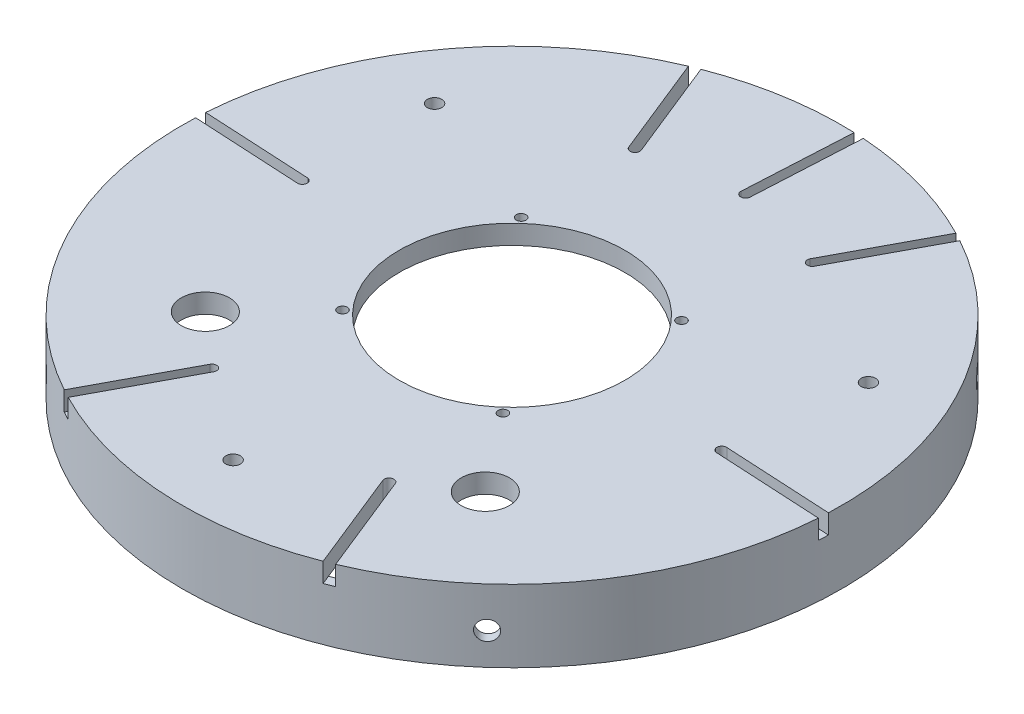
SolidWorks part; units mm, degrees
material "6061 Alloy"
ref_plane "Front Plane" through (0, 0, 0) normal (0, 0, 1) x (1, 0, 0)
ref_plane "Top Plane" through (0, 0, 0) normal (0, 1, 0) x (1, 0, 0)
ref_plane "Right Plane" through (0, 0, 0) normal (1, 0, 0) x (0, 0, -1)
sketch "Sketch1" plane through (0, 0, 0) normal (0, 1, 0) x (-0.9986, 0, -0.0535)
  line L0 (55.4987, 41.0091) -> (55.4987, 34.0091) construction
  line L2 (55.4987, -32.3449) -> (55.4987, -2.3278) construction
  circle A1 centre (55.4987, -32.3449) radius 68.37
  circle A3 centre (55.4987, -32.3449) radius 23.401
extrude "Boss-Extrude1" add sketch "Sketch1" along normal blind 2
sketch "Sketch3" plane through (0, 2, 0) normal (0, 1, 0) x (1, 0, 0)
  circle A0 centre (-53.6871, 35.2703) radius 68.37
  circle A1 centre (-53.6871, 35.2703) radius 66.37
extrude "Boss-Extrude2" add sketch "Sketch3" against normal blind 13
sketch "Sketch24" [suppressed] plane through (0, 4.3, 0) normal (0, 1, 0) x (1, 0, 0)
  line L0 (-34.4111, 2.0274) -> (-34.9466, -7.9582) construction
  line L1 (25.902, -11.2211) -> (26.4375, -1.2355) construction
  point P0 (-34.6788, -2.9654)
  point P1 (26.1698, -6.2283)
sketch "Sketch25" [suppressed] plane through (0, 0, 0) normal (0, -1, 0) x (1, 0, 0)
  point P0 (-34.6788, 2.9654)
  point P1 (26.1698, 6.2283)
ref_plane "Plane1" [suppressed] through (-0.258, 0, 4.8112) normal (0.0535, 0, -0.9986) x (-0.9986, 0, -0.0535)
sketch "Sketch29" [suppressed] plane through (0, 4.3, 0) normal (0, 1, 0) x (1, 0, 0)
  arc A0 (18.841, -0.8281) -> (-26.8146, 1.6201) centre (-4.2545, -4.5968) ccw construction
  arc A1 (-27.3501, -8.3656) -> (18.3055, -10.8138) centre (-4.2545, -4.5968) ccw construction
  point P0 (-3.0015, 18.7706)
  point P1 (-5.5076, -27.9643)
sketch "Sketch30" [suppressed] plane through (0, 0, 0) normal (0, -1, 0) x (1, 0, 0)
  point P0 (-5.5076, 27.9643)
  point P1 (-3.0015, -18.7706)
ref_plane "Plane2" [suppressed] through (-3.9965, 0, -0.2143) normal (-0.9986, 0, -0.0535) x (-0.0535, 0, 0.9986)
sketch "Sketch35" [suppressed] plane through (0, 0, 0) normal (0, 1, 0) x (1, 0, 0)
  line L0 (-3.8699, 2.5759) -> (-4.1232, -2.1473) construction
  line L1 (2.1036, -4.9378) -> (-2.6196, -4.6845) construction
  line L2 (20.5267, 17.662) -> (-4.2545, -4.5968) construction
  line L3 (-4.2545, -4.5968) -> (-31.1135, -28.7219) construction
  arc A1 (-27.3501, -8.3656) -> (18.3055, -10.8138) centre (-4.2545, -4.5968) ccw construction
  point P0 (-4.2545, -4.5968)
  point P8 (20.5267, 17.662)
  point P10 (-21.6638, -20.2341)
sketch "Sketch36" [suppressed] plane through (0, 4.3, 0) normal (0, 1, 0) x (1, 0, 0)
  point P0 (20.5267, 17.662)
ref_plane "Plane3" [suppressed] through (0.3855, 0, 0.4291) normal (0.6682, 0, 0.744) x (0.744, 0, -0.6682)
sketch "Sketch37" [suppressed] plane through (0, 4.3, 0) normal (0, 1, 0) x (1, 0, 0)
  line L1 (-26.6296, 20.3138) -> (-4.2545, -4.5968) construction
  line L2 (-4.2545, -4.5968) -> (20.7564, -32.4421) construction
  point P0 (-4.2545, -4.5968)
  point P7 (-26.6296, 20.3138)
sketch "Sketch39" [suppressed] plane through (0, 0, 0) normal (0, -1, 0) x (1, 0, 0)
  point P0 (-26.6296, -20.3138)
ref_plane "Plane4" [suppressed] through (-4.64, 0, 4.1677) normal (-0.744, 0, 0.6682) x (0.6682, 0, 0.744)
sketch "Sketch40" [suppressed] plane through (0.3855, 0, 0.4291) normal (0.6682, 0, 0.744) x (0.744, 0, -0.6682)
  circle A0 centre (-6.2369, -3.85) radius 2
extrude "Cut-Extrude27" [suppressed] cut sketch "Sketch40" against normal through all
pattern_circular "CirPattern2" [suppressed] count 4 over 360
sketch "Sketch58" plane through (0, 2, 0) normal (0, 1, 0) x (1, 0, 0)
  line L2 (-12.7238, 29.0656) -> (-12.2954, 37.0565)
  line L3 (-12.2954, 37.0565) -> (-7.3025, 36.7887)
  line L4 (-7.3025, 36.7887) -> (-7.731, 28.7979)
  line L5 (-7.731, 28.7979) -> (-12.7238, 29.0656)
sketch "Sketch60" plane through (0, 2, 0) normal (0, 1, 0) x (1, 0, 0)
  line L0 (-52.2437, 62.1872) -> (-55.1305, 8.3534) construction
  line L1 (-84.1539, 36.904) -> (-23.2203, 33.6365) construction
  line L4 (-73.7408, 17.2578) -> (-104.5394, -10.4059) construction
  line L5 (-53.6871, 35.2703) -> (-73.7408, 17.2578) construction
  line L6 (-71.6996, 55.324) -> (-99.3633, 86.1226) construction
  line L7 (-53.6871, 35.2703) -> (-71.6996, 55.324) construction
  line L8 (-33.6334, 53.2828) -> (-2.8348, 80.9464) construction
  line L9 (-53.6871, 35.2703) -> (-33.6334, 53.2828) construction
  line L10 (-35.6746, 15.2165) -> (-8.0109, -15.5821) construction
  line L11 (-53.6871, 35.2703) -> (-35.6746, 15.2165) construction
  line L12 (-73.7408, 17.2578) -> (-104.5394, -10.4059) construction
  line L13 (-53.6871, 35.2703) -> (-73.7408, 17.2578) construction
  arc A1 (-55.1305, 8.3534) -> (-80.604, 36.7136) centre (-53.6871, 35.2703) cw
sketch "Sketch62" plane through (0, 0, 0) normal (0, -1, 0) x (1, 0, 0)
  line L0 (-8.0109, 15.5821) -> (-99.3633, -86.1226) construction
  line L1 (-104.5394, 10.4059) -> (-2.8348, -80.9464) construction
  point P9 (-53.6871, -35.2703)
ref_plane "Plane5" through (-41.5069, 0, -46.2106) normal (0.6682, 0, 0.744) x (0.744, 0, -0.6682)
ref_plane "Plane6" through (-12.1802, 0, 10.9404) normal (0.744, 0, -0.6682) x (-0.6682, 0, -0.744)
sketch "Sketch63" plane through (-41.5069, 0, -46.2106) normal (0.6682, 0, 0.744) x (0.744, 0, -0.6682)
  line L0 (-84.7262, 0) -> (51.9818, 0) construction
  line L3 (-16.3722, 0) -> (-16.3722, -8.7) construction
  circle A0 centre (-16.3722, -4.35) radius 2
extrude "Cut-Extrude40" cut sketch "Sketch63" against normal through all and the other way through all
sketch "Sketch64" plane through (-12.1802, 0, 10.9404) normal (0.744, 0, -0.6682) x (-0.6682, 0, -0.744)
  line L0 (-6.2392, 0) -> (130.4688, 0) construction
  line L3 (62.1148, 0) -> (62.1148, -8.7) construction
  circle A0 centre (62.1148, -4.35) radius 2
extrude "Cut-Extrude41" cut sketch "Sketch64" against normal through all and the other way through all
sketch "Sketch65" plane through (0, 2, 0) normal (0, -1, 0) x (1, 0, 0)
  line L2 (1.1947, -31.5296) -> (-6.7555, -31.9265)
  line L3 (0.4048, -1118.9656) -> (-50.8954, -91.2006) construction
  line L4 (1.2944, -33.5271) -> (-6.7555, -33.9289)
  line L5 (-108.5689, -39.0109) -> (-100.6187, -38.6141)
  line L6 (-108.6686, -37.0134) -> (-100.6187, -36.6116)
  line L7 (-49.9465, -90.152) -> (-50.3433, -82.2019)
  line L8 (-51.944, -90.2517) -> (-52.3458, -82.2019)
  line L16 (-57.4277, 19.6115) -> (-57.0309, 11.6614) [skipped]
  line L17 (-55.4302, 19.7112) -> (-55.0284, 11.6614) [skipped]
  arc A2 (1.2944, -33.5271) -> (1.1947, -31.5296) centre (1.2445, -32.5284) ccw
  arc A3 (-6.7555, -33.9289) -> (-6.7555, -31.9265) centre (-6.8055, -32.9277) cw
  arc A4 (-51.944, -90.2517) -> (-49.9465, -90.152) centre (-50.9452, -90.2019) ccw
  arc A5 (-52.3458, -82.2019) -> (-50.3433, -82.2019) centre (-51.3445, -82.1519) cw
  arc A6 (-108.6686, -37.0134) -> (-108.5689, -39.0109) centre (-108.6187, -38.0121) ccw
  arc A7 (-100.6187, -36.6116) -> (-100.6187, -38.6141) centre (-100.5687, -37.6128) cw
  arc A16 (-55.4302, 19.7112) -> (-57.4277, 19.6115) centre (-56.429, 19.6614) ccw [skipped]
  arc A17 (-55.0284, 11.6614) -> (-57.0309, 11.6614) centre (-56.0297, 11.6114) cw [skipped]
  dimension "D1" = 4
sketch "Sketch67" plane through (0, 2, 0) normal (0, 1, 0) x (1, 0, 0)
  line L0 (-99.6611, 37.7404) -> (-7.7126, 32.8099) construction
  line L1 (-51.2218, 81.2445) -> (-56.1524, -10.704) construction
  line L2 (-47.8311, 125.7094) -> (-49.8283, 125.8165)
  line L3 (-144.1262, 41.1262) -> (-144.2333, 39.1291)
  line L4 (-99.6075, 38.739) -> (-144.1262, 41.1262)
  line L5 (-99.7146, 36.7419) -> (-144.2333, 39.1291)
  line L6 (-50.2184, 81.1907) -> (-47.8311, 125.7094)
  line L7 (-52.2155, 81.2978) -> (-49.8283, 125.8165)
  line L8 (36.752, 29.4143) -> (36.8591, 31.4114)
  line L9 (-7.7667, 31.8015) -> (36.752, 29.4143)
  line L10 (-7.6596, 33.7987) -> (36.8591, 31.4114)
  line L49 (-59.5431, -55.1689) -> (-57.5459, -55.276) [skipped]
  line L50 (-57.1558, -10.6501) -> (-59.5431, -55.1689) [skipped]
  line L51 (-55.1587, -10.7572) -> (-57.5459, -55.276) [skipped]
  arc A1 (-99.6075, 38.739) -> (-99.7146, 36.7419) centre (-99.6611, 37.7404) cw
  arc A2 (-50.2184, 81.1907) -> (-52.2155, 81.2978) centre (-51.2169, 81.2442) cw
  arc A3 (-7.7667, 31.8015) -> (-7.6596, 33.7987) centre (-7.7132, 32.8001) cw
  arc A8 (-57.1558, -10.6501) -> (-55.1587, -10.7572) centre (-56.1573, -10.7037) cw [skipped]
  dimension "D1" = 4
extrude "Cut-Extrude45" cut sketch "Sketch67" against normal blind 2
sketch "Sketch70" plane through (0, 2, 0) normal (0, 1, 0) x (1, 0, 0)
  line L0 (-51.2169, 81.2442) -> (-53.6871, 35.2703) construction
  line L1 (-99.6611, 37.7404) -> (-7.7132, 32.8001) construction
  line L2 (-53.6871, 35.2703) -> (-56.5307, -17.6534) construction
  circle A0 centre (-99.7745, 65.2862) radius 1.5
  circle A1 centre (-56.638, -19.6505) radius 1.5
  circle A2 centre (-4.6489, 60.1751) radius 1.5
  dimension "D1" = 3
  dimension "D2" = 3
sketch "Sketch72" plane through (0, 2, 0) normal (0, 1, 0) x (1, 0, 0)
  line L0 (-51.2169, 81.2442) -> (-56.638, -19.6505) construction
  line L1 (-99.6611, 37.7404) -> (-7.7132, 32.8001) construction
sketch "Sketch73" plane through (0, 2, 0) normal (0, -1, 0) x (1, 0, 0)
  circle A0 centre (-72.2141, -18.6326) radius 1
  circle A1 centre (-37.0495, -16.7433) radius 1
  circle A2 centre (-35.1601, -51.9079) radius 1
  circle A3 centre (-70.3247, -53.7973) radius 1
extrude "Cut-Extrude47" cut sketch "Sketch73" along normal blind 10
extrude "Cut-Extrude48" cut sketch "Sketch70" against normal blind 10
extrude "Cut-Extrude49" cut sketch "Sketch74" against normal blind 10
sketch "Sketch74" plane through (19.5625, 3, -2.0536) normal (0, 1, 0) x (1, 0, 0)
  line L0 (-73.2496, 33.2167) -> (-76.2005, -21.7041) construction
  line L1 (-73.2496, 33.2167) -> (-44.3242, -1.2553) construction
  line L2 (-73.2496, 33.2167) -> (-105.7022, 2.0425) construction
  circle A0 centre (-105.7022, 2.0425) radius 5
  circle A1 centre (-44.3242, -1.2553) radius 5
sketch "Sketch75" plane through (0, 2, 0) normal (0, 1, 0) x (1, 0, 0)
  line L0 (-50.0757, 102.5274) -> (-51.2185, 81.2443) construction
  line L1 (-120.9442, 38.8817) -> (13.57, 31.6588) construction
  line L2 (-86.2666, -23.6885) -> (-88.9936, -28.8014)
  line L3 (-22.8723, 95.1703) -> (-32.9078, 76.3546)
  line L4 (-21.1076, 94.229) -> (-31.1431, 75.4134)
  line L5 (-88.9936, -28.8014) -> (-87.2289, -29.7426)
  line L6 (-53.5602, 37.6331) -> (-58.8341, -60.585) construction
  line L7 (-52.5853, 35.2111) -> (-52.8048, 34.7997)
  line L8 (-84.5019, -24.6297) -> (-87.2289, -29.7426)
  line L9 (-79.7658, 97.3787) -> (-83.5737, 106.8386)
  line L10 (-53.5602, 37.6331) -> (-54.5694, 35.7409)
  line L11 (-77.9105, 98.1256) -> (-82.0529, 108.4166)
  line L12 (-79.7658, 97.3787) -> (-71.8029, 77.5967)
  line L13 (-22.8723, 95.1703) -> (-17.9091, 104.4757)
  line L14 (-77.9105, 98.1256) -> (-69.9475, 78.3435)
  line L15 (-27.6084, -26.8382) -> (-35.5714, -7.0562)
  line L16 (-21.1076, 94.229) -> (-18.0109, 100.0352)
  line L17 (-29.4638, -27.5851) -> (-37.4267, -7.803)
  line L18 (-29.4638, -27.5851) -> (-27.0828, -33.5)
  line L19 (-84.5019, -24.6297) -> (-74.4664, -5.8141)
  line L20 (-86.2666, -23.6885) -> (-76.2311, -4.8729)
  line L21 (-27.6084, -26.8382) -> (-25.2275, -32.7531)
  line L22 (-25.2275, -32.7531) -> (-27.0828, -33.5)
  line L23 (-83.5737, 106.8386) -> (-82.0529, 108.4166)
  line L24 (-17.9091, 104.4757) -> (-18.0109, 100.0352)
  arc A3 (-32.9078, 76.3546) -> (-31.1431, 75.4134) centre (-32.0254, 75.884) ccw
  arc A4 (-69.9475, 78.3435) -> (-71.8029, 77.5967) centre (-70.8752, 77.9701) cw
  arc A5 (-37.4267, -7.803) -> (-35.5714, -7.0562) centre (-36.499, -7.4296) cw
  arc A6 (-74.4664, -5.8141) -> (-76.2311, -4.8729) centre (-75.3488, -5.3435) ccw
extrude "Cut-Extrude51" cut sketch "Sketch75" against normal blind 2
sketch "Sketch80" plane through (0, 2, 0) normal (0, 1, 0) x (1, 0, 0)
  line L0 (-121.8978, 39.9343) -> (-99.6075, 38.739)
  line L1 (-122.0051, 37.9371) -> (-99.7146, 36.7419)
  line L2 (-78.2871, 99.0613) -> (-69.9475, 78.3435)
  line L3 (-80.1424, 98.3145) -> (-71.8029, 77.5967)
  line L4 (-51.0202, 103.5882) -> (-52.2155, 81.2978)
  line L5 (-49.0231, 103.481) -> (-50.2184, 81.1907)
  line L6 (-22.3976, 96.0603) -> (-32.9078, 76.3546)
  line L7 (-20.6329, 95.119) -> (-31.1431, 75.4134)
  line L8 (-20.6329, 95.119) -> (-31.1431, 75.4134) construction
  line L9 (14.6309, 32.6034) -> (-7.6596, 33.7987)
  line L10 (-7.7667, 31.8015) -> (14.5236, 30.6063)
  line L11 (-86.7413, -24.5785) -> (-76.2311, -4.8729)
  line L12 (-74.4664, -5.8141) -> (-84.9766, -25.5197)
  line L13 (-37.4267, -7.803) -> (-29.0871, -28.5208)
  line L14 (-35.5714, -7.0562) -> (-27.2318, -27.7739)
  arc A0 (-80.1424, 98.3145) -> (-121.8978, 39.9343) centre (-53.6871, 35.2703) ccw
  circle A1 centre (-99.7745, 65.2862) radius 1.5
  circle A2 centre (-4.6489, 60.1751) radius 1.5
  circle A3 centre (-24.7617, 0.7983) radius 5
  circle A4 centre (-86.1397, 4.0961) radius 5
  circle A5 centre (-72.2141, 18.6326) radius 1
  circle A6 centre (-53.6871, 35.2703) radius 23.401
  circle A7 centre (-37.0495, 16.7433) radius 1
  circle A8 centre (-35.1601, 51.9079) radius 1
  circle A9 centre (-70.3247, 53.7973) radius 1
  arc A10 (-32.9078, 76.3546) -> (-31.1431, 75.4134) centre (-32.0254, 75.884) ccw construction
  circle A11 centre (-56.638, -19.6505) radius 1.5
  arc A12 (-7.7667, 31.8015) -> (-7.6596, 33.7987) centre (-7.7132, 32.8001) cw
  arc A13 (-32.9078, 76.3546) -> (-31.1431, 75.4134) centre (-32.0254, 75.884) ccw
  arc A14 (-52.2155, 81.2978) -> (-50.2184, 81.1907) centre (-51.2169, 81.2442) ccw
  arc A15 (-69.9475, 78.3435) -> (-71.8029, 77.5967) centre (-70.8752, 77.9701) cw
  arc A16 (-99.6075, 38.739) -> (-99.7146, 36.7419) centre (-99.6611, 37.7404) cw
  arc A17 (-74.4664, -5.8141) -> (-76.2311, -4.8729) centre (-75.3488, -5.3435) ccw
  arc A18 (-51.0202, 103.5882) -> (-78.2871, 99.0613) centre (-53.6871, 35.2703) ccw
  arc A19 (-76.2311, -4.8729) -> (-74.4664, -5.8141) centre (-75.3488, -5.3435) cw
  arc A20 (-35.5714, -7.0562) -> (-37.4267, -7.803) centre (-36.499, -7.4296) ccw
  arc A21 (-22.3976, 96.0603) -> (-49.0231, 103.481) centre (-53.6871, 35.2703) ccw
  arc A22 (14.6309, 32.6034) -> (-20.6329, 95.119) centre (-53.6871, 35.2703) ccw
  arc A23 (-27.2318, -27.7739) -> (14.5236, 30.6063) centre (-53.6871, 35.2703) ccw
  arc A24 (-84.9766, -25.5197) -> (-29.0871, -28.5208) centre (-53.6871, 35.2703) ccw
  arc A25 (-122.0051, 37.9371) -> (-86.7413, -24.5785) centre (-53.6871, 35.2703) ccw
  circle M1 centre (-24.7617, 0.7983) radius 5
  circle M2 centre (-86.1397, 4.0961) radius 5
  circle M3 centre (-4.6489, 60.1751) radius 1.5
  circle M4 centre (-99.7745, 65.2862) radius 1.5
  circle M5 centre (-56.638, -19.6505) radius 1.5
  circle M6 centre (-35.1601, 51.9079) radius 1
  circle M7 centre (-72.2141, 18.6326) radius 1
  circle M8 centre (-53.6871, 35.2703) radius 23.401
  circle M9 centre (-37.0495, 16.7433) radius 1
  circle M10 centre (-70.3247, 53.7973) radius 1
  arc M11 (-37.4267, -7.803) -> (-35.5714, -7.0562) centre (-36.499, -7.4296) cw
  line M12 (-35.5714, -7.0562) -> (-27.2318, -27.7739)
  arc M13 (-27.2318, -27.7739) -> (14.5236, 30.6063) centre (-53.6871, 35.2703) ccw
  line M14 (14.5236, 30.6063) -> (-7.7667, 31.8015)
  arc M15 (-7.7667, 31.8015) -> (-7.6596, 33.7987) centre (-7.7132, 32.8001) cw
  line M16 (-7.6596, 33.7987) -> (14.6309, 32.6034)
  arc M17 (14.6309, 32.6034) -> (-20.6329, 95.119) centre (-53.6871, 35.2703) ccw
  line M18 (-20.6329, 95.119) -> (-31.1431, 75.4134)
  arc M19 (-31.1431, 75.4134) -> (-32.9078, 76.3546) centre (-32.0254, 75.884) cw
  line M20 (-32.9078, 76.3546) -> (-22.3976, 96.0603)
  arc M21 (-22.3976, 96.0603) -> (-49.0231, 103.481) centre (-53.6871, 35.2703) ccw
  line M22 (-49.0231, 103.481) -> (-50.2184, 81.1907)
  arc M23 (-50.2184, 81.1907) -> (-52.2155, 81.2978) centre (-51.2169, 81.2442) cw
  line M24 (-52.2155, 81.2978) -> (-51.0202, 103.5882)
  arc M25 (-51.0202, 103.5882) -> (-78.2871, 99.0613) centre (-53.6871, 35.2703) ccw
  line M26 (-78.2871, 99.0613) -> (-69.9475, 78.3435)
  arc M27 (-69.9475, 78.3435) -> (-71.8029, 77.5967) centre (-70.8752, 77.9701) cw
  line M28 (-71.8029, 77.5967) -> (-80.1424, 98.3145)
  arc M29 (-80.1424, 98.3145) -> (-121.8978, 39.9343) centre (-53.6871, 35.2703) ccw
  line M30 (-121.8978, 39.9343) -> (-99.6075, 38.739)
  arc M31 (-99.6075, 38.739) -> (-99.7146, 36.7419) centre (-99.6611, 37.7404) cw
  line M32 (-99.7146, 36.7419) -> (-122.0051, 37.9371)
  arc M33 (-122.0051, 37.9371) -> (-86.7413, -24.5785) centre (-53.6871, 35.2703) ccw
  line M34 (-86.7413, -24.5785) -> (-76.2311, -4.8729)
  arc M35 (-76.2311, -4.8729) -> (-74.4664, -5.8141) centre (-75.3488, -5.3435) cw
  line M36 (-74.4664, -5.8141) -> (-84.9766, -25.5197)
  arc M37 (-84.9766, -25.5197) -> (-29.0871, -28.5208) centre (-53.6871, 35.2703) ccw
  line M38 (-29.0871, -28.5208) -> (-37.4267, -7.803)
extrude "Boss-Extrude4" add sketch "Sketch80" along normal blind 2 contours M38 M11 M12 M13 M14 M15 M16 M17 M18 M19 M20 M21 M22 M23 M24 M25 M26 M27 M28 M29 M30 M31 M32 M33 M34 M35 M36 M37 M2 M4 M6 M8 M10 M9 M7 M5 M3 M1
